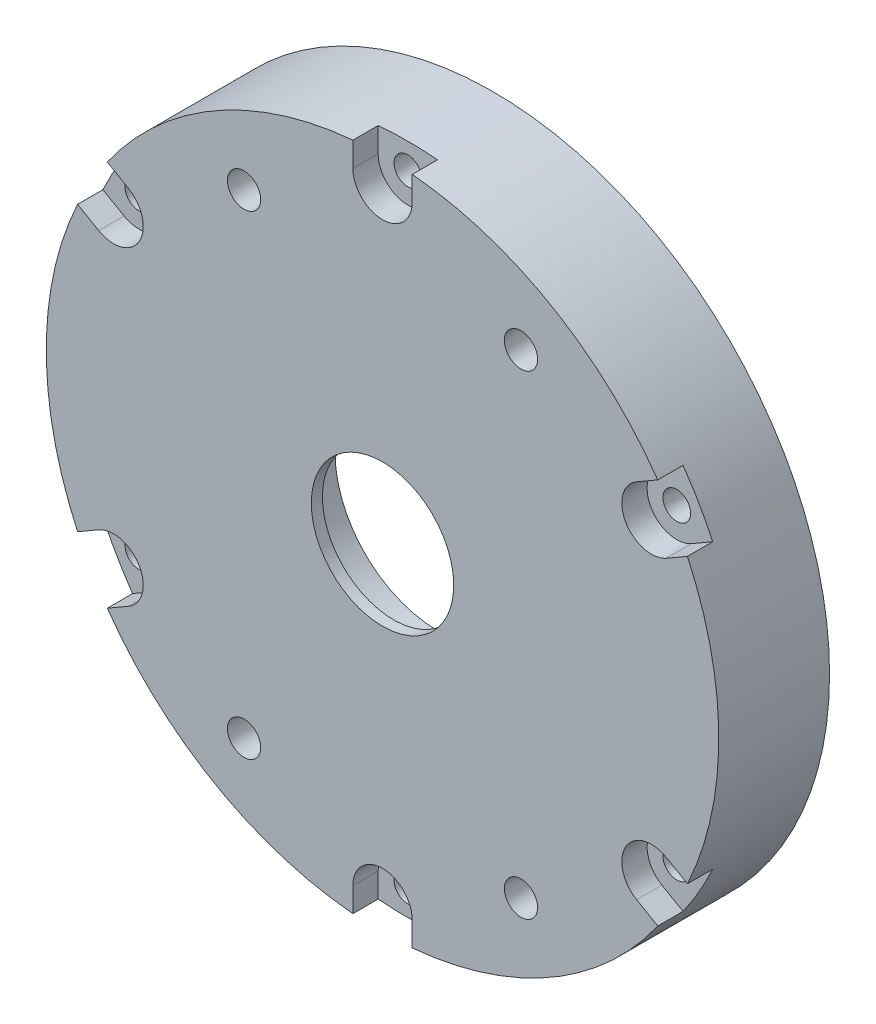
SolidWorks part; units mm, degrees
ref_plane "Plano frontal" through (0, 0, 0) normal (0, 0, 1) x (1, 0, 0)
ref_plane "Plano superior" through (0, 0, 0) normal (0, 1, 0) x (1, 0, 0)
ref_plane "Plano direito" through (0, 0, 0) normal (1, 0, 0) x (0, 0, -1)
sketch "Esboço1" plane through (0, 0, 0) normal (0, 0, 1) x (1, 0, 0)
  circle A0 centre (0, 0) radius 42.5
  dimension "D1" = 85
extrude "Ressalto-extrusão1" add sketch "Esboço1" along normal blind 14
sketch "Esboço3" plane through (0, 0, 0) normal (0, 1, 0) x (1, 0, 0)
  line L0 (0, 0) -> (0, -14)
  line L1 (-42.5, -14) -> (42.5, -14) construction
  line L2 (0, -14) -> (-9, -14)
  line L3 (-9, -14) -> (-9, -12.6)
  line L4 (-9, -12.6) -> (-12, -12.6)
  line L5 (-12, -12.6) -> (-12, -12)
  line L6 (-12, -12) -> (-13, -12)
  line L7 (-13, -12) -> (-13, -7)
  line L8 (-13, -7) -> (-36, -7)
  line L9 (-36, -7) -> (-36, 0)
  line L10 (42.5, 0) -> (-42.5, 0) construction
  line L11 (-36, 0) -> (0, 0)
  dimension "D1" = 9
  dimension "D2" = 1.4
  dimension "D3" = 3
  dimension "D4" = 0.6
  dimension "D5" = 1
  dimension "D6" = 5
  dimension "D7" = 23
revolve "Corte-Revolução1" cut sketch "Esboço3" angle 360 about L0
sketch "Esboço4" plane through (0, 0, 14) normal (0, 0, 1) x (1, 0, 0)
  line L0 (0, 0) -> (0, 42.5) construction
  line L1 (-3.75, 39.25) -> (-3.75, 42.3342)
  line L2 (3.75, 39.25) -> (3.75, 42.3342)
  circle A0 centre (0, 0) radius 42.5 construction
  arc A1 (-3.75, 39.25) -> (3.75, 39.25) centre (0, 39.25) ccw
  arc A2 (3.75, 42.3342) -> (-3.75, 42.3342) centre (0, 0) ccw
  dimension "D1" = 7.5
  dimension "D2" = 39.25
extrude "Corte-extrusão1" cut sketch "Esboço4" against normal blind 3.2
sketch "Esboço5" plane through (0, 0, 10.8) normal (0, 0, 1) x (1, 0, 0)
  circle A0 centre (0, 39.25) radius 1.75
  dimension "D1" = 3.5
extrude "Corte-extrusão2" cut sketch "Esboço5" against normal through all
pattern_circular "PadrãoCircular1" count 6 over 360 about axis through (0, 0, 0) along (0, 0, 1) of "Corte-extrusão1", "Corte-extrusão2"
sketch "Esboço6" plane through (0, 0, 14) normal (0, 0, 1) x (1, 0, 0)
  line L1 (17.5, -30) -> (-17.5, -30) construction
  line L2 (17.5, -30) -> (17.5, 30) construction
  line L3 (17.5, 30) -> (-17.5, 30) construction
  line L4 (-17.5, -30) -> (-17.5, 30) construction
  line L5 (17.5, -30) -> (-17.5, 30) construction
  line L6 (17.5, 30) -> (-17.5, -30) construction
  circle A0 centre (-17.5, 30) radius 2.1
  circle A1 centre (17.5, 30) radius 2.1
  circle A2 centre (17.5, -30) radius 2.1
  circle A3 centre (-17.5, -30) radius 2.1
  point P0 (0, 0)
  dimension "D3" = 4.2
  dimension "D1" = 60
  dimension "D2" = 35
extrude "Corte-extrusão3" cut sketch "Esboço6" against normal blind 5
